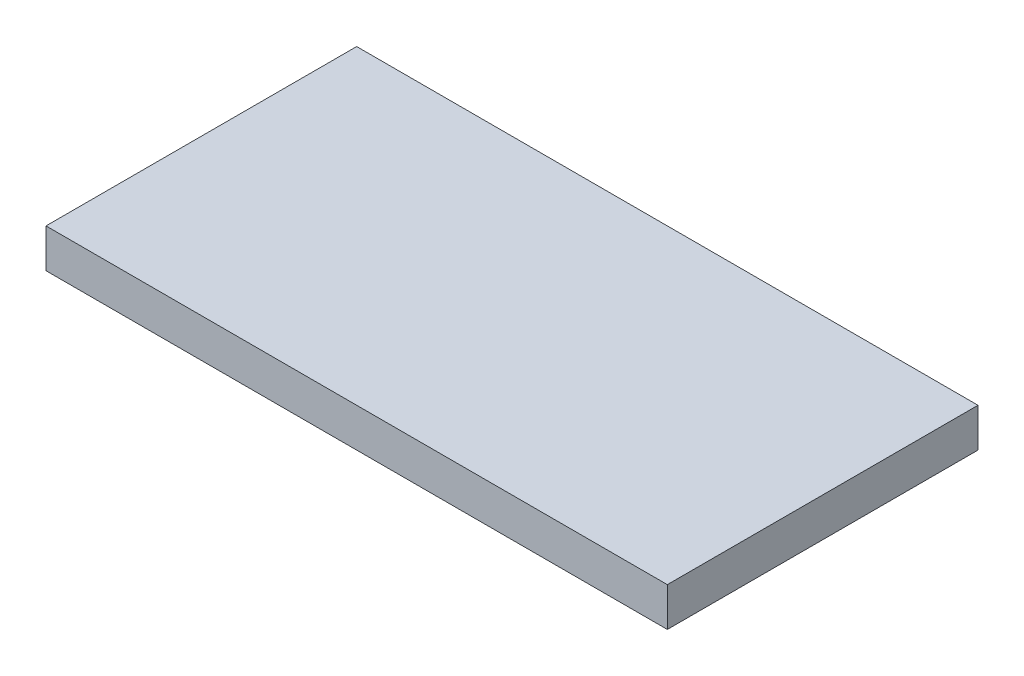
SolidWorks part; units mm, degrees
ref_plane "Alzado" through (0, 0, 0) normal (0, 0, 1) x (1, 0, 0)
ref_plane "Planta" through (0, 0, 0) normal (0, 1, 0) x (1, 0, 0)
ref_plane "Vista lateral" through (0, 0, 0) normal (1, 0, 0) x (0, 0, -1)
sketch "Croquis1" plane through (0, 0, 0) normal (0, 1, 0) x (1, 0, 0)
  line L0 (0, 11.3953) -> (0, -9.7674) construction
  line L1 (-12.8488, 0) -> (15.5814, 0) construction
  line L3 (-80, -40) -> (80, -40)
  line L4 (-80, -40) -> (-80, 40)
  line L5 (-80, 40) -> (80, 40)
  line L6 (80, -40) -> (80, 40)
  line L7 (-80, -40) -> (80, 40) construction
  line L8 (-80, 40) -> (80, -40) construction
  point P5 (0, 0)
  dimension "D1" = 80
  dimension "D2" = 160
extrude "Saliente-Extruir1" add sketch "Croquis1" along normal blind 10
